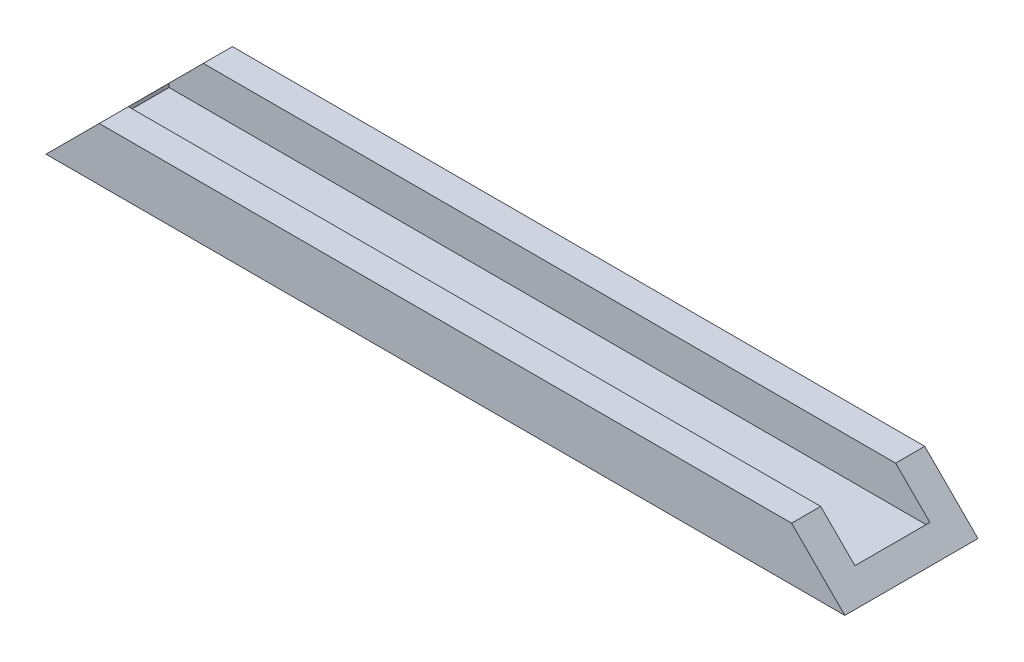
SolidWorks part; units mm, degrees
material "Copper"
ref_plane "Front Plane" through (0, 0, 0) normal (0, 0, 1) x (1, 0, 0)
ref_plane "Top Plane" through (0, 0, 0) normal (0, 1, 0) x (1, 0, 0)
ref_plane "Right Plane" through (0, 0, 0) normal (1, 0, 0) x (0, 0, -1)
sketch "Sketch1" plane through (0, 0, 0) normal (0, 1, 0) x (1, 0, 0)
  line L1 (0, 0) -> (133.35, 0)
  line L2 (0, 0) -> (0, 22.225)
  line L3 (0, 22.225) -> (133.35, 22.225)
  line L4 (133.35, 0) -> (133.35, 22.225)
  dimension "D1" = 133.35
  dimension "D2" = 22.225
extrude "Base Extrude" add sketch "Sketch1" along normal blind 8.89
sketch "Sketch3" plane through (0, 8.89, 0) normal (0, 1, 0) x (1, 0, 0)
  line L1 (3.175, 17.3673) -> (130.175, 17.3672)
  line L2 (3.175, 17.3673) -> (3.175, 4.8577)
  line L3 (3.175, 4.8577) -> (130.175, 4.8577)
  line L4 (130.175, 17.3672) -> (130.175, 4.8577)
  line L5 (0, 22.225) -> (0, 0) construction
  line L6 (133.35, 0) -> (133.35, 22.225) construction
  line L8 (3.175, 11.1125) -> (130.175, 11.1125) construction
  line L9 (133.35, 11.1125) -> (0, 11.1125) construction
  dimension "D1" = 12.5095
  dimension "D2" = 127
  dimension "D3" = 3.175
extrude "Piece Cut" cut sketch "Sketch3" against normal blind 6.35
sketch "Sketch4" plane through (0, 0, -22.225) normal (0, 0, -1) x (-1, 0, 0)
  line L0 (0, 0) -> (-8.89, 8.89)
  line L1 (-133.35, 8.89) -> (0, 8.89) construction
  line L2 (0, 0) -> (0, 8.89)
  line L3 (0, 8.89) -> (-8.89, 8.89)
  line L4 (-66.675, 0) -> (-66.675, 8.89) construction
  line L5 (-133.35, 0) -> (0, 0) construction
  line L6 (-133.35, 8.89) -> (-124.46, 8.89)
  line L7 (-133.35, 0) -> (-133.35, 8.89)
  line L8 (-133.35, 0) -> (-124.46, 8.89)
  dimension "D1" = 45
extrude "Corner Cut" cut sketch "Sketch4" against normal through all
